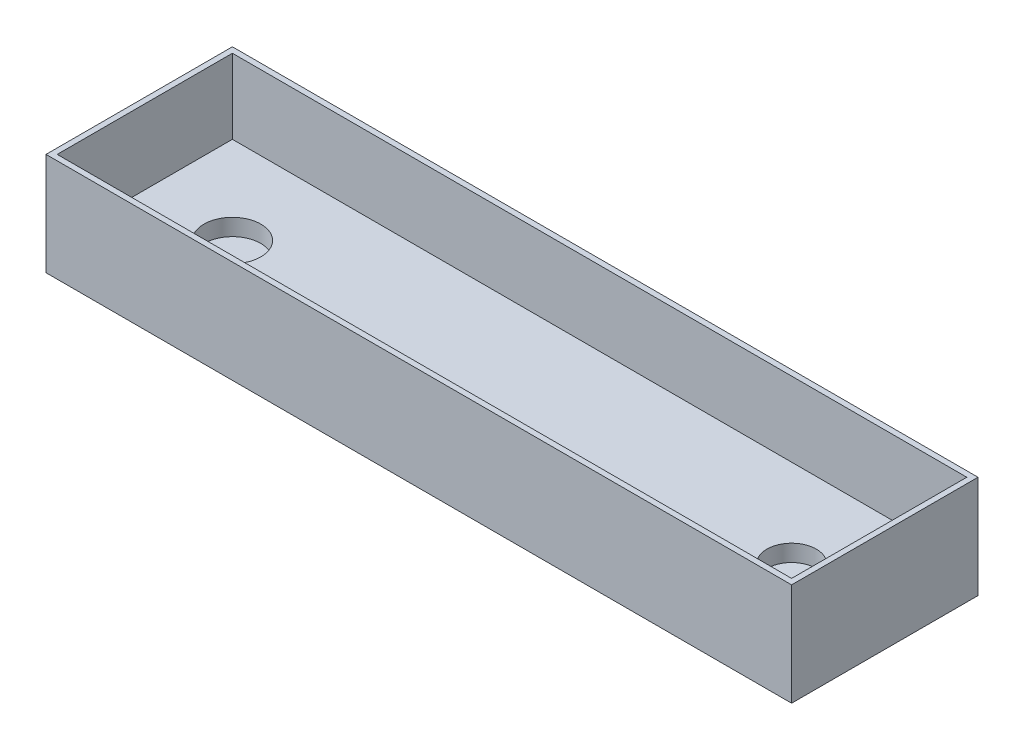
SolidWorks part; units mm, degrees
ref_plane "Front Plane" through (0, 0, 0) normal (0, 0, 1) x (1, 0, 0)
ref_plane "Top Plane" through (0, 0, 0) normal (0, 1, 0) x (1, 0, 0)
ref_plane "Right Plane" through (0, 0, 0) normal (1, 0, 0) x (0, 0, -1)
sketch "Sketch1" plane through (0, 0, 0) normal (0, 1, 0) x (1, 0, 0)
  line L1 (-200, 50) -> (200, 50)
  line L2 (-200, 50) -> (-200, -50)
  line L3 (-200, -50) -> (200, -50)
  line L4 (200, 50) -> (200, -50)
  dimension "D1" = 50
  dimension "D2" = 50
  dimension "D3" = 200
  dimension "D4" = 200
extrude "Boss-Extrude1" add sketch "Sketch1" along normal blind 15
sketch "Sketch2" plane through (0, 15, 0) normal (0, 1, 0) x (1, 0, 0)
  circle A0 centre (-150, 0) radius 15.25
  circle A1 centre (150, 0) radius 13.25
  dimension "D3" = 30.5
  dimension "D4" = 26.5
  dimension "D1" = 150
  dimension "D2" = 150
extrude "Cut-Extrude1" cut sketch "Sketch2" against normal blind 9
sketch "Sketch3" plane through (0, 15, 0) normal (0, 1, 0) x (1, 0, 0)
  line L1 (-200, 50) -> (200, 50)
  line L2 (-200, 50) -> (-200, -50)
  line L3 (-200, -50) -> (200, -50)
  line L4 (200, 50) -> (200, -50)
  line L5 (-197, -47) -> (197, -47)
  line L6 (-197, -47) -> (-197, 47)
  line L7 (-197, 47) -> (197, 47)
  line L8 (197, -47) -> (197, 47)
  line L9 (-197, -47) -> (197, 47) construction
  line L10 (-197, 47) -> (197, -47) construction
  point P4 (0, 0)
  dimension "D1" = 3
  dimension "D2" = 3
extrude "Boss-Extrude2" add sketch "Sketch3" along normal blind 40
equation "\"D2@Sketch1\"=\"D1@Sketch1\""
equation "\"D4@Sketch1\"=\"D3@Sketch1\""
equation "\"D2@Sketch2\"=\"D1@Sketch2\""
